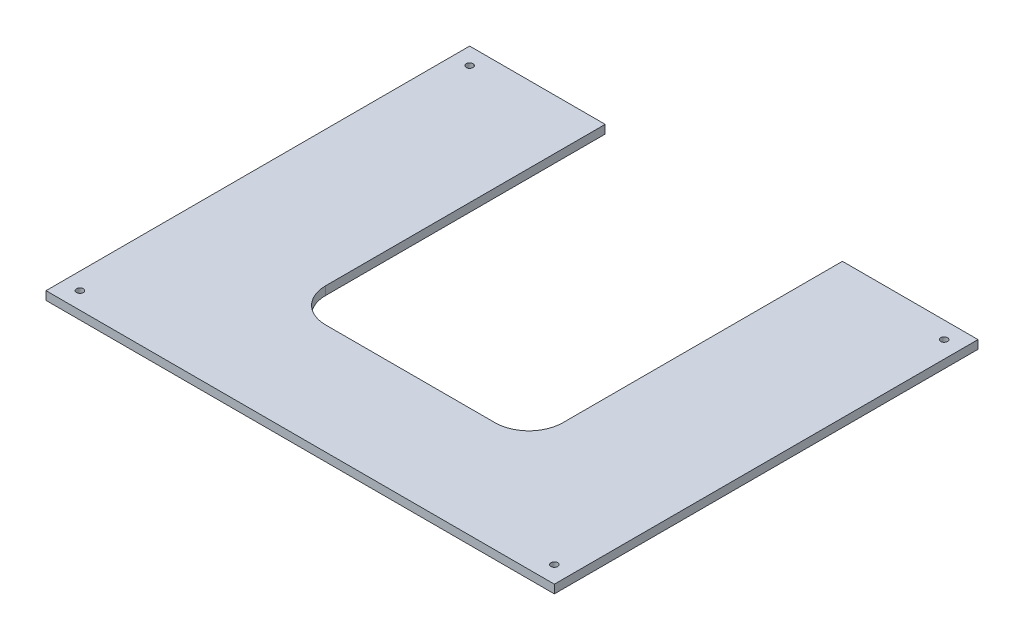
SolidWorks part; units mm, degrees
ref_plane "前视基准面" through (0, 0, 0) normal (0, 0, 1) x (1, 0, 0)
ref_plane "上视基准面" through (0, 0, 0) normal (0, 1, 0) x (1, 0, 0)
ref_plane "右视基准面" through (0, 0, 0) normal (1, 0, 0) x (0, 0, -1)
sketch "Sketch1" plane through (0, 0, 0) normal (0, 1, 0) x (1, 0, 0)
  line L0 (-140, -125) -> (-140, 125) construction
  line L1 (-150, -125) -> (150, -125)
  line L2 (-150, -125) -> (-150, 125)
  line L3 (-150, 125) -> (150, 125)
  line L4 (150, -125) -> (150, 125)
  line L5 (-150, -125) -> (150, 125) construction
  line L6 (-150, 125) -> (150, -125) construction
  line L7 (0, 0) -> (0, 125) construction
  line L8 (0, 0) -> (-150, 0) construction
  circle A0 centre (-140, -115) radius 2
  circle A1 centre (-140, 115) radius 2
  circle A2 centre (140, -115) radius 2
  circle A3 centre (140, 115) radius 2
  point P0 (0, 0)
  dimension "D4" = 4
  dimension "D5" = 10
  dimension "D1" = 300
  dimension "D2" = 250
  dimension "D3" = 10
extrude "Boss-Extrude1" add sketch "Sketch1" along normal blind 5
sketch "Sketch2" plane through (0, 5, 0) normal (0, 1, 0) x (1, 0, 0)
  line L0 (150, 125) -> (-150, 125) construction
  line L1 (-70, 125) -> (70, 125)
  line L2 (-70, 125) -> (-70, -60)
  line L3 (-70, -60) -> (70, -60)
  line L4 (70, 125) -> (70, -60)
  line L5 (0, -60) -> (0, 125) construction
  dimension "D1" = 140
  dimension "D2" = 185
extrude "Cut-Extrude1" cut sketch "Sketch2" against normal through all
fillet "Fillet1" radius 20 2 edges at (70, 2.5, 60) (-70, 2.5, 60)
